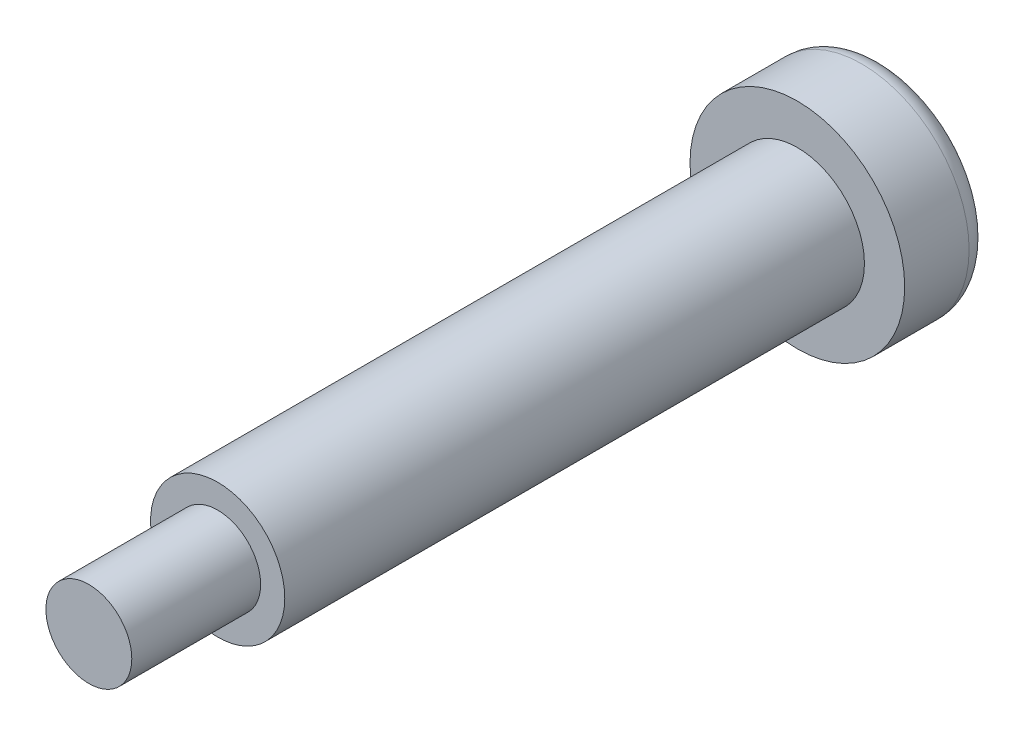
SolidWorks part; units mm, degrees
ref_plane "Ön Düzlem" through (0, 0, 0) normal (0, 0, 1) x (1, 0, 0)
ref_plane "Üst Düzlem" through (0, 0, 0) normal (0, 1, 0) x (1, 0, 0)
ref_plane "Sağ Düzlem" through (0, 0, 0) normal (1, 0, 0) x (0, 0, -1)
sketch "Çizim1" plane through (0, 0, 0) normal (0, 0, 1) x (1, 0, 0)
  circle A0 centre (0, 0) radius 5
  dimension "D1" = 10
extrude "Yükseklik-Ekstrüzyon1" add sketch "Çizim1" along normal mid plane 4
sketch "Çizim2" plane through (0, 0, 0) normal (0, 0, 1) x (1, 0, 0)
  line L1 (2.3094, 0) -> (1.1547, 2)
  line L2 (1.1547, 2) -> (-1.1547, 2)
  line L3 (-1.1547, 2) -> (-2.3094, 0)
  line L4 (-2.3094, 0) -> (-1.1547, -2)
  line L5 (-1.1547, -2) -> (1.1547, -2)
  line L6 (1.1547, -2) -> (2.3094, 0)
  circle A0 centre (0, 0) radius 2 construction
  dimension "D1" = 4
extrude "Yükseklik-Ekstrüzyon2" add sketch "Çizim2" along normal mid plane 4
sketch "Çizim3" plane through (0, 0, 2) normal (0, 0, 1) x (1, 0, 0)
  circle A0 centre (0, 0) radius 3.125
  dimension "D1" = 6.25
extrude "Yükseklik-Ekstrüzyon3" add sketch "Çizim3" along normal blind 27
sketch "Çizim4" plane through (0, 0, 29) normal (0, 0, 1) x (1, 0, 0)
  circle A0 centre (0, 0) radius 2
  dimension "D1" = 4
extrude "Yükseklik-Ekstrüzyon4" add sketch "Çizim4" along normal blind 6
cosmetic thread "Kozmetik Diş Açma1" parameters "D2"=3.22
fillet "Radyus1" radius 1 1 edges at (5, 0, -2)
sketch "Çizim5" plane through (0, 0, -2) normal (0, 0, -1) x (-1, 0, 0)
  line L1 (2.3094, 0) -> (1.1547, 2)
  line L2 (1.1547, 2) -> (-1.1547, 2)
  line L3 (-1.1547, 2) -> (-2.3094, 0)
  line L4 (-2.3094, 0) -> (-1.1547, -2)
  line L5 (-1.1547, -2) -> (1.1547, -2)
  line L6 (1.1547, -2) -> (2.3094, 0)
  circle A0 centre (0, 0) radius 2 construction
  dimension "D1" = 4
extrude "Kes-Ekstrüzyon1" cut sketch "Çizim5" against normal blind 2.5
